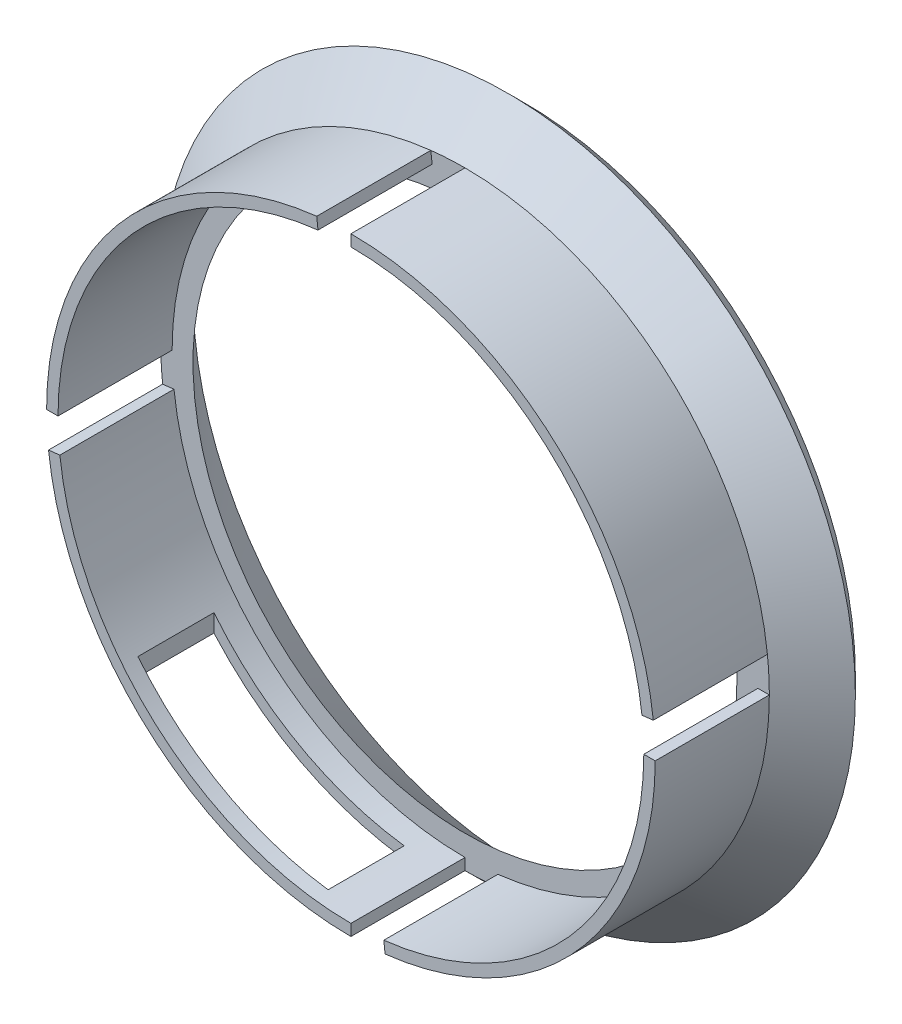
SolidWorks part; units mm, degrees
material "PLA"
ref_plane "Alzado" through (0, 0, 0) normal (0, 0, 1) x (1, 0, 0)
ref_plane "Planta" through (0, 0, 0) normal (0, 1, 0) x (1, 0, 0)
ref_plane "Vista lateral" through (0, 0, 0) normal (1, 0, 0) x (0, 0, -1)
sketch "Croquis1" plane through (0, 0, 0) normal (0, 0, 1) x (1, 0, 0)
  line L0 (0, 40) -> (0, 38.5)
  line L1 (-4.4929, 39.7469) -> (-4.3244, 38.2564)
  line L2 (-38.5, 0) -> (-40, 0)
  line L3 (-39.7469, -4.4929) -> (-38.2564, -4.3244)
  line L4 (0, -40) -> (0, -38.5)
  line L5 (4.4929, -39.7469) -> (4.3244, -38.2564)
  line L6 (38.5, 0) -> (40, 0)
  line L7 (39.7469, 4.4929) -> (38.2564, 4.3244)
  circle A0 centre (0, 0) radius 40
  circle A1 centre (0, 0) radius 38.5
  dimension "D1" = 77
  dimension "0" = 80
  dimension "D2" = 4.5
  dimension "D3" = 4.5
  dimension "D4" = 4.5
  dimension "D5" = 4.5
extrude "Saliente-Extruir1" add sketch "Croquis1" along normal blind 15 contours A1 L1 A0 L2 | A1 L3 A0 L4 | A1 L7 A0 L0 | A1 L5 A0 L6
sketch "Croquis2" plane through (0, 0, 0) normal (0, 1, 0) x (1, 0, 0)
  line L0 (-40, 0) -> (-45.6569, 5.6569)
  line L1 (-45.6569, 5.6569) -> (-43.5355, 7.7782)
  line L2 (-43.5355, 7.7782) -> (-35.7574, 0)
  line L3 (-4.4929, 0) -> (-40, 0) construction
  line L4 (0, 0) -> (0, 20.2639) construction
  line L5 (-35.7574, 0) -> (-40, 0)
  dimension "D1" = 3
  dimension "D2" = 11
  dimension "D3" = 45
revolve "Revolución1" add sketch "Croquis2" angle 360 about L4
sketch "Croquis3" plane through (0, 0, 0) normal (0, 1, 0) x (1, 0, 0)
  line L1 (-30, -3) -> (-5, -3)
  line L2 (-30, -3) -> (-30, -13)
  line L3 (-30, -13) -> (-5, -13)
  line L4 (-5, -3) -> (-5, -13)
  line L8 (-39.7469, 0) -> (0, 0) construction
  line L9 (40, -15) -> (40, 0) construction
  dimension "D1" = 3
  dimension "D2" = 25
  dimension "D3" = 10
  dimension "D4" = 45
extrude "Cortar-Extruir1" cut sketch "Croquis3" against normal up to next
